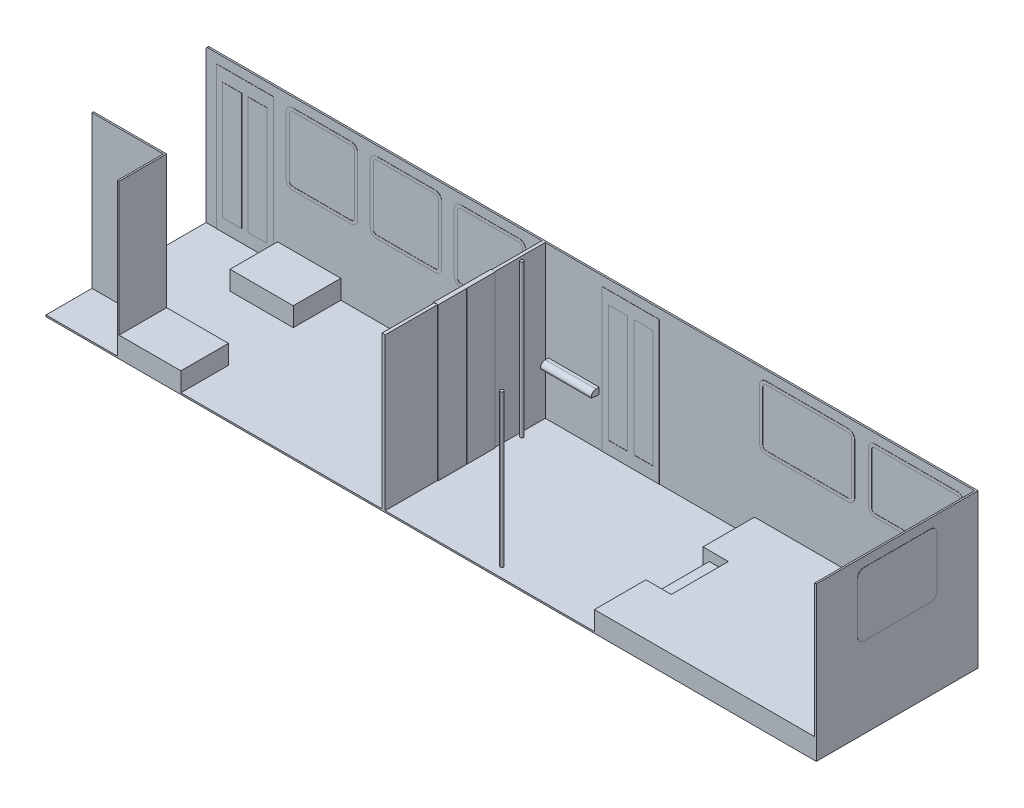
SolidWorks part; units mm, degrees
ref_plane "Front Plane" through (0, 0, 0) normal (0, 0, 1) x (1, 0, 0)
ref_plane "Top Plane" through (0, 0, 0) normal (0, 1, 0) x (1, 0, 0)
ref_plane "Right Plane" through (0, 0, 0) normal (1, 0, 0) x (0, 0, -1)
sketch "Sketch2" plane through (0, 0, 0) normal (0, 1, 0) x (1, 0, 0)
  line L1 (-6172.2, 1295.4) -> (6172.2, 1295.4)
  line L2 (-6172.2, 1295.4) -> (-6172.2, -1295.4)
  line L3 (-6172.2, -1295.4) -> (6172.2, -1295.4)
  line L4 (6172.2, 1295.4) -> (6172.2, -1295.4)
  line L5 (-6172.2, 1295.4) -> (6172.2, -1295.4) construction
  line L6 (-6172.2, -1295.4) -> (6172.2, 1295.4) construction
  point P0 (0, 0)
extrude "Boss-Extrude1" add sketch "Sketch2" along normal blind 25.4
sketch "Sketch3" plane through (0, 25.4, 0) normal (0, 1, 0) x (1, 0, 0)
  line L0 (-6172.2, -1295.4) -> (6172.2, -1295.4) construction
  line L4 (-787.4, 1295.4) -> (-787.4, -1295.4)
  line L6 (-787.4, 1295.4) -> (-736.6, 1295.4)
  line L7 (-787.4, 1295.4) -> (-787.4, -1295.4)
  line L8 (-787.4, -1295.4) -> (-736.6, -1295.4)
  line L9 (-736.6, 1295.4) -> (-736.6, -1295.4)
  line M2 (6172.2, 1295.4) -> (-6172.2, 1295.4)
  line M4 (-6172.2, -1295.4) -> (6172.2, -1295.4)
extrude "Boss-Extrude2" add sketch "Sketch3" along normal blind 2440.94 contours L9 L4 M2 M4
sketch "Sketch4" plane through (-736.6, 0, 0) normal (1, 0, 0) x (0, 0, -1)
  line L0 (1295.4, 2466.34) -> (-1295.4, 2466.34) construction
  line L1 (0, 2466.34) -> (457.2, 2466.34)
  line L2 (0, 2466.34) -> (0, 25.4)
  line L3 (0, 25.4) -> (457.2, 25.4)
  line L4 (457.2, 2466.34) -> (457.2, 25.4)
  line L5 (1295.4, 25.4) -> (-1295.4, 25.4) construction
  line L7 (0, 2466.34) -> (-457.2, 2466.34)
  line L8 (0, 2466.34) -> (0, 25.4)
  line L9 (0, 25.4) -> (-457.2, 25.4)
  line L10 (-457.2, 2466.34) -> (-457.2, 25.4)
  line M9 (-1295.4, 25.4) -> (1295.4, 25.4)
  line M11 (1295.4, 2466.34) -> (-1295.4, 2466.34)
extrude "Boss-Extrude4" add sketch "Sketch4" against normal blind 71.12 from offset 10.16 separate body contours L10 L2 M11 M9
sketch "Sketch5" plane through (-726.44, 0, 0) normal (1, 0, 0) x (0, 0, -1)
  line L1 (457.2, 2466.34) -> (-457.2, 2466.34) construction
  line L2 (-457.2, 25.4) -> (457.2, 25.4) construction
  line L3 (0, 25.4) -> (-6.35, 25.4)
  line L4 (-6.35, 25.4) -> (-6.35, 2466.34)
  line L5 (-6.35, 2466.34) -> (0, 2466.34)
  line L6 (0, 2466.34) -> (6.35, 2466.34)
  line L7 (6.35, 2466.34) -> (6.35, 25.4)
  line L8 (6.35, 25.4) -> (0, 25.4)
extrude "Cut-Extrude1" cut sketch "Sketch5" against normal blind 5.08
sketch "Sketch6" plane through (-731.52, 0, 0) normal (1, 0, 0) x (0, 0, -1)
  line L0 (-6.35, 25.4) -> (6.35, 25.4) construction
  line L1 (6.35, 2466.34) -> (-6.35, 2466.34)
  line L2 (6.35, 2466.34) -> (6.35, 25.4)
  line L3 (6.35, 25.4) -> (-6.35, 25.4)
  line L4 (-6.35, 2466.34) -> (-6.35, 25.4)
  line L5 (-6.35, 2466.34) -> (-6.35, 25.4) construction
extrude "Cut-Extrude2" cut sketch "Sketch6" along normal blind 5.08 from offset 66.04 offset against normal yes
sketch "Sketch8" plane through (0, 2466.34, 0) normal (0, 1, 0) x (1, 0, 0)
  line L0 (-797.56, 457.2) -> (-797.56, 6.35) construction
  line L1 (-726.44, -457.2) -> (-797.56, -457.2)
  line L2 (-726.44, -457.2) -> (-726.44, 457.2)
  line L3 (-726.44, 457.2) -> (-797.56, 457.2)
  line L4 (-797.56, -457.2) -> (-797.56, 457.2)
extrude "Boss-Extrude5" add sketch "Sketch8" along normal blind 2.54
sketch "Sketch9" plane through (0, 0, -1295.4) normal (0, 0, -1) x (-1, 0, 0)
  line L1 (736.6, 2466.34) -> (787.4, 2466.34)
  line L2 (736.6, 2466.34) -> (736.6, 25.4)
  line L3 (736.6, 25.4) -> (787.4, 25.4)
  line L4 (787.4, 2466.34) -> (787.4, 25.4)
extrude "Cut-Extrude4" cut sketch "Sketch9" against normal blind 25.4
sketch "Sketch11" plane through (0, 25.4, 0) normal (0, 1, 0) x (1, 0, 0)
  line L0 (6172.2, -1295.4) -> (6172.2, 1295.4) construction
  line L1 (-6172.2, 1295.4) -> (6172.2, 1295.4)
  line L2 (-6172.2, 1295.4) -> (-6172.2, 1270)
  line L3 (-6172.2, 1270) -> (6172.2, 1270)
  line L4 (6172.2, 1295.4) -> (6172.2, 1270)
  line L6 (-1128.2325, -4255.065) -> (-638.6774, -4255.065)
  line L7 (-1128.2325, -4255.065) -> (-1128.2325, -7837.6362)
  line L8 (-1128.2325, -7837.6362) -> (-638.6774, -7837.6362)
  line L9 (-638.6774, -4255.065) -> (-638.6774, -7837.6362)
extrude "Boss-Extrude6" add sketch "Sketch11" along normal blind 2438.4 contours L2 L1 L4 L3
fillet "Fillet1" radius 25.4 1 edges at (-6172.2, 2463.8, -1282.7)
sketch "Sketch12" plane through (0, 0, -1270) normal (0, 0, 1) x (1, 0, 0)
  line L0 (-6172.2, 25.4) -> (-787.4, 25.4) construction
  line L1 (-6003.7041, 25.4) -> (-5089.3041, 25.4)
  line L2 (-6003.7041, 25.4) -> (-6003.7041, 2311.4)
  line L3 (-6003.7041, 2311.4) -> (-5089.3041, 2311.4)
  line L4 (-5089.3041, 25.4) -> (-5089.3041, 2311.4)
extrude "Boss-Extrude7" add sketch "Sketch12" against normal blind 30.48 from offset 2.54 separate body contours L2 L1 L4 L3
sketch "Sketch13" plane through (0, 0, -1267.46) normal (0, 0, 1) x (1, 0, 0)
  line L0 (-6003.7041, 2311.4) -> (-5902.1041, 2311.4) construction
  line L1 (-6003.7041, 2311.4) -> (-5089.3041, 2311.4) construction
  line L2 (-5902.1041, 2108.2) -> (-5597.3041, 2108.2)
  line L3 (-5495.7041, 2108.2) -> (-5190.9041, 2108.2)
  line L4 (-5190.9041, 228.6) -> (-5190.9041, 2108.2) construction
  line L5 (-5190.9041, 228.6) -> (-5495.7041, 228.6)
  line L6 (-5597.3041, 228.6) -> (-5902.1041, 228.6)
  line L8 (-5902.1041, 2108.2) -> (-5902.1041, 228.6)
  line L10 (-5190.9041, 2108.2) -> (-5190.9041, 228.6)
  line L11 (-5597.3041, 228.6) -> (-5597.3041, 2108.2)
  line L13 (-5495.7041, 2108.2) -> (-5495.7041, 228.6)
extrude "Cut-Extrude5" cut sketch "Sketch13" against normal blind 99.06
sketch "Sketch17" plane through (0, 0, -1267.46) normal (0, 0, 1) x (1, 0, 0)
  line L1 (-5902.1041, 2108.2) -> (-5597.3041, 2108.2)
  line L2 (-5902.1041, 2108.2) -> (-5902.1041, 228.6)
  line L3 (-5902.1041, 228.6) -> (-5597.3041, 228.6)
  line L4 (-5597.3041, 2108.2) -> (-5597.3041, 228.6)
  line L5 (-5495.7041, 228.6) -> (-5190.9041, 228.6)
  line L6 (-5495.7041, 228.6) -> (-5495.7041, 2108.2)
  line L7 (-5495.7041, 2108.2) -> (-5190.9041, 2108.2)
  line L8 (-5190.9041, 228.6) -> (-5190.9041, 2108.2)
extrude "Boss-Extrude9" add sketch "Sketch17" against normal blind 25.4 from offset 2.54
sketch "Sketch20" plane through (0, 25.4, 0) normal (0, 1, 0) x (1, 0, 0)
  line L0 (-736.6, -1295.4) -> (6172.2, -1295.4) construction
  line L1 (6172.2, 1270) -> (2616.2, 1270)
  line L2 (6172.2, 1270) -> (6172.2, -1295.4)
  line L3 (6172.2, -1295.4) -> (2616.2, -1295.4)
  line L4 (2616.2, 1270) -> (2616.2, -1295.4)
extrude "Boss-Extrude10" add sketch "Sketch20" along normal blind 304.8
sketch "Sketch21" plane through (2616.2, 0, 0) normal (-1, 0, 0) x (0, 0, 1)
  line L0 (-1270, 330.2) -> (1295.4, 330.2) construction
  line L1 (12.7, 330.2) -> (12.7, 25.4) construction
  line L2 (-1270, 25.4) -> (1295.4, 25.4) construction
  line L4 (-444.5, 25.4) -> (469.9, 25.4)
  line L5 (-444.5, 25.4) -> (-444.5, 330.2)
  line L6 (-444.5, 330.2) -> (469.9, 330.2)
  line L7 (469.9, 25.4) -> (469.9, 330.2)
  line L8 (-444.5, 25.4) -> (469.9, 330.2) construction
  line L9 (-444.5, 330.2) -> (469.9, 25.4) construction
  point P8 (12.7, 177.8)
extrude "Cut-Extrude6" cut sketch "Sketch21" against normal blind 101.6
sketch "Sketch22" plane through (2717.8, 0, 0) normal (-1, 0, 0) x (0, 0, 1)
  line L0 (469.9, 25.4) -> (469.9, 330.2) construction
  line L1 (-444.5, 330.2) -> (469.9, 330.2)
  line L2 (-444.5, 330.2) -> (-444.5, 177.8)
  line L3 (-444.5, 177.8) -> (469.9, 177.8)
  line L4 (469.9, 330.2) -> (469.9, 177.8)
extrude "Cut-Extrude7" cut sketch "Sketch22" against normal blind 304.8
sketch "Sketch25" plane through (0, 0, -1270) normal (0, 0, 1) x (1, 0, 0)
  line L0 (-736.6, 25.4) -> (177.8, 25.4) construction
  line L1 (-736.6, 25.4) -> (2616.2, 25.4) construction
  line L3 (177.8, 25.4) -> (1092.2, 25.4)
  line L4 (177.8, 25.4) -> (177.8, 2311.4)
  line L5 (177.8, 2311.4) -> (1092.2, 2311.4)
  line L6 (1092.2, 25.4) -> (1092.2, 2311.4)
  line L11 (584.2, 228.6) -> (279.4, 228.6)
  line L12 (584.2, 228.6) -> (584.2, 2108.2)
  line L13 (584.2, 2108.2) -> (279.4, 2108.2)
  line L14 (279.4, 228.6) -> (279.4, 2108.2)
  line L15 (685.8, 2108.2) -> (990.6, 2108.2)
  line L16 (685.8, 2108.2) -> (685.8, 228.6)
  line L17 (685.8, 228.6) -> (990.6, 228.6)
  line L18 (990.6, 2108.2) -> (990.6, 228.6)
  point P8 (0, 0)
  point P9 (0, 0)
  point P10 (0, 0)
  point P13 (0, 0)
  point P14 (0, 0)
  point P22 (0, 0)
  point P23 (0, 0)
extrude "Boss-Extrude12" add sketch "Sketch25" against normal blind 27.94 from offset 2.54 separate body
sketch "Sketch27" plane through (0, 0, -1267.46) normal (0, 0, 1) x (1, 0, 0)
  line L1 (279.4, 2108.2) -> (584.2, 2108.2)
  line L2 (279.4, 2108.2) -> (279.4, 228.6)
  line L3 (279.4, 228.6) -> (584.2, 228.6)
  line L4 (584.2, 2108.2) -> (584.2, 228.6)
  line L5 (685.8, 228.6) -> (990.6, 228.6)
  line L6 (685.8, 228.6) -> (685.8, 2108.2)
  line L7 (685.8, 2108.2) -> (990.6, 2108.2)
  line L8 (990.6, 228.6) -> (990.6, 2108.2)
extrude "Boss-Extrude13" add sketch "Sketch27" against normal blind 27.94 from offset 2.54 contours L2 L1 L4 L3 offset against normal yes
sketch "Sketch28" plane through (0, 0, -1270) normal (0, 0, 1) x (1, 0, 0)
  line L0 (-736.6, 889) -> (-685.8, 889)
  line L2 (-401.0106, 787.4) -> (177.8, 787.4)
  line L3 (177.8, 25.4) -> (177.8, 2311.4) construction
  line L4 (177.8, 787.4) -> (177.8, 889)
  line L5 (177.8, 889) -> (-736.6, 889)
  line L6 (-736.6, 2463.8) -> (-736.6, 25.4) construction
  line L7 (-736.6, 889) -> (-736.6, 787.4)
  line L8 (-736.6, 787.4) -> (-401.0106, 787.4)
  line L9 (-685.8, 889) -> (-685.8, 787.4)
  line L10 (-685.8, 787.4) -> (127, 787.4)
  line L11 (127, 787.4) -> (127, 889)
  line L12 (-685.8, 889) -> (127, 889)
extrude "Boss-Extrude17" add sketch "Sketch28" along normal blind 127 contours L2 L11 L5 L9 L8
fillet "Fillet3" radius 76.2 1 edges at (-279.4, 889, -1143)
chamfer "Chamfer2" distance 101.6 distance2 12.7 1 edges at (-279.4, 787.4, -1143)
sketch "Sketch31" plane through (0, 25.4, 0) normal (0, 1, 0) x (1, 0, 0)
  circle A0 centre (-670.5546, 827.918) radius 25.4
  point P2 (-595.0728, 966.3361)
  point P3 (-629.9364, 737.5636)
  point P4 (-685.3283, 823.8649)
  point P5 (-670.5546, 827.918)
extrude "Boss-Extrude18" add sketch "Sketch31" along normal blind 2438.4 contours A0
sketch "Sketch32" plane through (0, 0, -1270) normal (0, 0, 1) x (1, 0, 0)
  line L0 (-5089.3041, 2311.4) -> (-787.4, 2311.4) construction
  line L1 (-787.4, 25.4) -> (-787.4, 2463.8) construction
  line L2 (-5089.3041, 2311.4) -> (-4886.1041, 2311.4) construction
  line L3 (-3743.1041, 1168.4) -> (-3539.9041, 1168.4) construction
  line L4 (-4784.5041, 2311.4) -> (-3844.7041, 2311.4)
  line L5 (-4886.1041, 2209.8) -> (-4886.1041, 1270)
  line L6 (-4784.5041, 1168.4) -> (-3844.7041, 1168.4)
  line L7 (-3743.1041, 2209.8) -> (-3743.1041, 1270)
  line L8 (-2396.9041, 1168.4) -> (-2193.7041, 1168.4) construction
  line L9 (-3438.3041, 1168.4) -> (-2498.5041, 1168.4)
  line L10 (-3539.9041, 1270) -> (-3539.9041, 2209.8)
  line L11 (-3438.3041, 2311.4) -> (-2498.5041, 2311.4)
  line L12 (-2396.9041, 1270) -> (-2396.9041, 2209.8)
  line L13 (-4835.3041, 2209.8) -> (-4835.3041, 1270)
  line L14 (-2092.1041, 1168.4) -> (-1152.3041, 1168.4)
  line L15 (-2193.7041, 1270) -> (-2193.7041, 2209.8)
  line L16 (-2092.1041, 2311.4) -> (-1152.3041, 2311.4)
  line L17 (-1050.7041, 1270) -> (-1050.7041, 2209.8)
  line L18 (-4784.5041, 1219.2) -> (-3844.7041, 1219.2)
  line L19 (-3793.9041, 2209.8) -> (-3793.9041, 1270)
  line L20 (-4784.5041, 2260.6) -> (-3844.7041, 2260.6)
  line L21 (-3489.1041, 1270) -> (-3489.1041, 2209.8)
  line L22 (-3438.3041, 2260.6) -> (-2498.5041, 2260.6)
  line L23 (-2447.7041, 1270) -> (-2447.7041, 2209.8)
  line L24 (-3438.3041, 1219.2) -> (-2498.5041, 1219.2)
  line L25 (-2142.9041, 1270) -> (-2142.9041, 2209.8)
  line L26 (-2092.1041, 2260.6) -> (-1152.3041, 2260.6)
  line L27 (-1101.5041, 1270) -> (-1101.5041, 2209.8)
  line L28 (-2092.1041, 1219.2) -> (-1152.3041, 1219.2)
  arc A0 (-4886.1041, 2209.8) -> (-4784.5041, 2311.4) centre (-4784.5041, 2209.8) cw
  arc A1 (-3844.7041, 1168.4) -> (-3743.1041, 1270) centre (-3844.7041, 1270) ccw
  arc A2 (-4886.1041, 1270) -> (-4784.5041, 1168.4) centre (-4784.5041, 1270) ccw
  arc A3 (-3844.7041, 2311.4) -> (-3743.1041, 2209.8) centre (-3844.7041, 2209.8) cw
  arc A4 (-1152.3041, 2311.4) -> (-1050.7041, 2209.8) centre (-1152.3041, 2209.8) cw
  arc A5 (-1152.3041, 1168.4) -> (-1050.7041, 1270) centre (-1152.3041, 1270) ccw
  arc A6 (-2193.7041, 1270) -> (-2092.1041, 1168.4) centre (-2092.1041, 1270) ccw
  arc A7 (-2193.7041, 2209.8) -> (-2092.1041, 2311.4) centre (-2092.1041, 2209.8) cw
  arc A8 (-2498.5041, 2311.4) -> (-2396.9041, 2209.8) centre (-2498.5041, 2209.8) cw
  arc A9 (-2498.5041, 1168.4) -> (-2396.9041, 1270) centre (-2498.5041, 1270) ccw
  arc A10 (-3539.9041, 1270) -> (-3438.3041, 1168.4) centre (-3438.3041, 1270) ccw
  arc A11 (-3539.9041, 2209.8) -> (-3438.3041, 2311.4) centre (-3438.3041, 2209.8) cw
  arc A12 (-4835.3041, 1270) -> (-4784.5041, 1219.2) centre (-4784.5041, 1270) ccw
  arc A13 (-3844.7041, 1219.2) -> (-3793.9041, 1270) centre (-3844.7041, 1270) ccw
  arc A14 (-3844.7041, 2260.6) -> (-3793.9041, 2209.8) centre (-3844.7041, 2209.8) cw
  arc A15 (-4835.3041, 2209.8) -> (-4784.5041, 2260.6) centre (-4784.5041, 2209.8) cw
  arc A16 (-3489.1041, 2209.8) -> (-3438.3041, 2260.6) centre (-3438.3041, 2209.8) cw
  arc A17 (-2498.5041, 2260.6) -> (-2447.7041, 2209.8) centre (-2498.5041, 2209.8) cw
  arc A18 (-2498.5041, 1219.2) -> (-2447.7041, 1270) centre (-2498.5041, 1270) ccw
  arc A19 (-3489.1041, 1270) -> (-3438.3041, 1219.2) centre (-3438.3041, 1270) ccw
  arc A20 (-2142.9041, 2209.8) -> (-2092.1041, 2260.6) centre (-2092.1041, 2209.8) cw
  arc A21 (-1152.3041, 2260.6) -> (-1101.5041, 2209.8) centre (-1152.3041, 2209.8) cw
  arc A22 (-1152.3041, 1219.2) -> (-1101.5041, 1270) centre (-1152.3041, 1270) ccw
  arc A23 (-2142.9041, 1270) -> (-2092.1041, 1219.2) centre (-2092.1041, 1270) ccw
  point P17 (0, 0)
  point P30 (-1050.7041, 2311.4)
  point P40 (-2396.9041, 2311.4)
  dimension "D1" = 101.6
  dimension "D2" = 101.6
  dimension "D3" = 101.6
  dimension "D4" = 50.8
  dimension "D5" = 50.8
  dimension "D6" = 50.8
extrude "Boss-Extrude19" add sketch "Sketch32" against normal blind 30.48 from offset 2.54 contours A11 L10 A10 L9 A9 L12 A8 L11 | A7 L15 A6 L14 A5 L17 A4 L16 | L5 A2 L6 A1 L7 A3 L4 A0
sketch3d "3DSketch1" plane through (0, 0, 0) normal (0, 0, 1) x (1, 0, 0)
sketch3d "3DSketch2" plane through (0, 0, 0) normal (0, 0, 1) x (1, 0, 0)
sketch "Sketch34" plane through (0, 0, -1267.46) normal (0, 0, 1) x (1, 0, 0)
  line L12 (-4835.3041, 2209.8) -> (-4835.3041, 1270)
  line L13 (-4784.5041, 1219.2) -> (-3844.7041, 1219.2)
  line L14 (-3793.9041, 1270) -> (-3793.9041, 2209.8)
  line L15 (-3844.7041, 2260.6) -> (-4784.5041, 2260.6)
  arc A12 (-4784.5041, 2260.6) -> (-4835.3041, 2209.8) centre (-4784.5041, 2209.8) ccw
  arc A13 (-4835.3041, 1270) -> (-4784.5041, 1219.2) centre (-4784.5041, 1270) ccw
  arc A14 (-3844.7041, 1219.2) -> (-3793.9041, 1270) centre (-3844.7041, 1270) ccw
  arc A15 (-3793.9041, 2209.8) -> (-3844.7041, 2260.6) centre (-3844.7041, 2209.8) ccw
extrude "Cut-Extrude8" cut sketch "Sketch34" against normal blind 2.54
sketch "Sketch35" plane through (0, 0, -1270) normal (0, 0, 1) x (1, 0, 0)
  line L1 (6172.2, 2463.8) -> (6172.2, 330.2) construction
  line L2 (6172.2, 2311.4) -> (5969, 2311.4) construction
  line L4 (5867.4, 2311.4) -> (4546.6, 2311.4)
  line L5 (5969, 2209.8) -> (5969, 1397)
  line L6 (5867.4, 1295.4) -> (4546.6, 1295.4)
  line L7 (4445, 2209.8) -> (4445, 1397)
  line L10 (4122.1853, 1295.4) -> (2801.3853, 1295.4)
  line L11 (4223.7853, 1397) -> (4223.7853, 2209.8)
  line L12 (4122.1853, 2311.4) -> (2801.3853, 2311.4)
  line L13 (2699.7853, 1397) -> (2699.7853, 2209.8)
  arc A0 (5969, 2209.8) -> (5867.4, 2311.4) centre (5867.4, 2209.8) ccw
  arc A1 (5969, 1397) -> (5867.4, 1295.4) centre (5867.4, 1397) cw
  arc A2 (4546.6, 1295.4) -> (4445, 1397) centre (4546.6, 1397) cw
  arc A3 (4546.6, 2311.4) -> (4445, 2209.8) centre (4546.6, 2209.8) ccw
  arc A4 (4223.7853, 2209.8) -> (4122.1853, 2311.4) centre (4122.1853, 2209.8) ccw
  arc A5 (4223.7853, 1397) -> (4122.1853, 1295.4) centre (4122.1853, 1397) cw
  arc A6 (2801.3853, 1295.4) -> (2699.7853, 1397) centre (2801.3853, 1397) cw
  arc A7 (2801.3853, 2311.4) -> (2699.7853, 2209.8) centre (2801.3853, 2209.8) ccw
  dimension "D1" = 101.6
extrude "Boss-Extrude22" add sketch "Sketch35" against normal blind 30.48 from offset 2.54
sketch "Sketch37" plane through (0, 0, -1267.46) normal (0, 0, 1) x (1, 0, 0)
  line L8 (4122.1853, 2260.6) -> (2801.3853, 2260.6)
  line L9 (2750.5853, 2209.8) -> (2750.5853, 1397)
  line L10 (2801.3853, 1346.2) -> (4122.1853, 1346.2)
  line L11 (4172.9853, 1397) -> (4172.9853, 2209.8)
  line L12 (4122.1853, 2260.6) -> (2801.3853, 2260.6)
  line L13 (2750.5853, 2209.8) -> (2750.5853, 1397)
  line L14 (2801.3853, 1346.2) -> (4122.1853, 1346.2)
  line L15 (4172.9853, 1397) -> (4172.9853, 2209.8)
  line L20 (5867.4, 2260.6) -> (4546.6, 2260.6)
  line L21 (4495.8, 2209.8) -> (4495.8, 1397)
  line L22 (4546.6, 1346.2) -> (5867.4, 1346.2)
  line L23 (5918.2, 1397) -> (5918.2, 2209.8)
  line L24 (5867.4, 2260.6) -> (4546.6, 2260.6)
  line L25 (4495.8, 2209.8) -> (4495.8, 1397)
  line L26 (4546.6, 1346.2) -> (5867.4, 1346.2)
  line L27 (5918.2, 1397) -> (5918.2, 2209.8)
  arc A8 (4172.9853, 2209.8) -> (4122.1853, 2260.6) centre (4122.1853, 2209.8) ccw
  arc A9 (2801.3853, 2260.6) -> (2750.5853, 2209.8) centre (2801.3853, 2209.8) ccw
  arc A10 (2750.5853, 1397) -> (2801.3853, 1346.2) centre (2801.3853, 1397) ccw
  arc A11 (4122.1853, 1346.2) -> (4172.9853, 1397) centre (4122.1853, 1397) ccw
  arc A12 (4172.9853, 2209.8) -> (4122.1853, 2260.6) centre (4122.1853, 2209.8) ccw
  arc A13 (2801.3853, 2260.6) -> (2750.5853, 2209.8) centre (2801.3853, 2209.8) ccw
  arc A14 (2750.5853, 1397) -> (2801.3853, 1346.2) centre (2801.3853, 1397) ccw
  arc A15 (4122.1853, 1346.2) -> (4172.9853, 1397) centre (4122.1853, 1397) ccw
  arc A20 (5918.2, 2209.8) -> (5867.4, 2260.6) centre (5867.4, 2209.8) ccw
  arc A21 (4546.6, 2260.6) -> (4495.8, 2209.8) centre (4546.6, 2209.8) ccw
  arc A22 (4495.8, 1397) -> (4546.6, 1346.2) centre (4546.6, 1397) ccw
  arc A23 (5867.4, 1346.2) -> (5918.2, 1397) centre (5867.4, 1397) ccw
  arc A24 (5918.2, 2209.8) -> (5867.4, 2260.6) centre (5867.4, 2209.8) ccw
  arc A25 (4546.6, 2260.6) -> (4495.8, 2209.8) centre (4546.6, 2209.8) ccw
  arc A26 (4495.8, 1397) -> (4546.6, 1346.2) centre (4546.6, 1397) ccw
  arc A27 (5867.4, 1346.2) -> (5918.2, 1397) centre (5867.4, 1397) ccw
  dimension "D1" = 50.8
  dimension "D2" = 50.8
extrude "Cut-Extrude10" cut sketch "Sketch37" against normal blind 2.54 contours L26 A27 L27 A24 L24 A25 L25 A26 | A12 L12 A13 L13 A14 L14 A15 L15
sketch "Sketch38" plane through (0, 25.4, 0) normal (0, 1, 0) x (1, 0, 0)
  circle A0 centre (969.6512, -1131.5574) radius 25.4
  point P2 (913.361, -1027.1569)
  point P3 (910.198, -884.2055)
  point P4 (945.0703, -858.1775)
  point P5 (929.3007, -695.3816)
  point P6 (962.8331, -1078.8647)
  point P7 (0, 0)
  point P8 (969.6512, -1131.5574)
extrude "Boss-Extrude23" add sketch "Sketch38" along normal blind 2438.4
sketch "Sketch39" plane through (0, 25.4, 0) normal (0, 1, 0) x (1, 0, 0)
  line L0 (-6172.2, 1270) -> (-5026.3967, 1270) construction
  line L1 (-5089.3041, 1270) -> (-787.4, 1270) construction
  line L2 (-5026.3967, 1270) -> (-5026.3967, -1295.4) construction
  line L3 (-6172.2, -1295.4) -> (-787.4, -1295.4) construction
  line L5 (-5026.3967, 1270) -> (-4013.2, 1270)
  line L6 (-5026.3967, 1270) -> (-5026.3967, 508)
  line L7 (-5026.3967, 508) -> (-4013.2, 508)
  line L8 (-4013.2, 1270) -> (-4013.2, 508)
  line L9 (-5026.3967, -1295.4) -> (-4010.3967, -1295.4)
  line L10 (-5026.3967, -1295.4) -> (-5026.3967, -533.4)
  line L11 (-5026.3967, -533.4) -> (-4010.3967, -533.4)
  line L12 (-4010.3967, -1295.4) -> (-4010.3967, -533.4)
extrude "Boss-Extrude24" add sketch "Sketch39" along normal blind 304.8
sketch "Sketch41" plane through (0, 330.2, 0) normal (0, 1, 0) x (1, 0, 0)
  line L0 (-5026.3967, -1295.4) -> (-4010.3967, -1295.4) construction
  line L1 (-5026.3967, -533.4) -> (-5000.9967, -533.4)
  line L2 (-5026.3967, -533.4) -> (-5026.3967, -1295.4)
  line L3 (-5026.3967, -1295.4) -> (-5000.9967, -1295.4)
  line L4 (-5000.9967, -533.4) -> (-5000.9967, -1295.4)
extrude "Boss-Extrude25" add sketch "Sketch41" along normal blind 2133.6 separate body
sketch "Sketch42" plane through (0, 25.4, 0) normal (0, 1, 0) x (1, 0, 0)
  line L0 (-6172.2, 1270) -> (-6172.2, -1295.4) construction
  line L1 (-5026.3967, -533.4) -> (-6172.2, -533.4)
  line L2 (-5026.3967, -533.4) -> (-5026.3967, -558.8)
  line L3 (-5026.3967, -558.8) -> (-6172.2, -558.8)
  line L4 (-6172.2, -533.4) -> (-6172.2, -558.8)
extrude "Boss-Extrude26" add sketch "Sketch42" along normal blind 2438.4 separate body
sketch "Sketch43" plane through (0, 330.2, 0) normal (0, 1, 0) x (1, 0, 0)
  line L0 (6172.2, 1270) -> (2616.2, 1270) construction
  line L1 (6172.2, -1295.4) -> (6146.8, -1295.4)
  line L2 (6172.2, -1295.4) -> (6172.2, 1270)
  line L3 (6172.2, 1270) -> (6146.8, 1270)
  line L4 (6146.8, -1295.4) -> (6146.8, 1270)
extrude "Boss-Extrude27" add sketch "Sketch43" along normal blind 2133.6
sketch "Sketch44" plane through (6146.8, 0, 0) normal (-1, 0, 0) x (0, 0, 1)
  line L0 (-1270, 2463.8) -> (12.7, 2463.8) construction
  line L1 (-1270, 2463.8) -> (1295.4, 2463.8) construction
  line L2 (12.7, 2463.8) -> (12.7, 2311.4) construction
  line L3 (12.7, 2311.4) -> (635, 2311.4) construction
  line L5 (533.4, 2311.4) -> (-533.4, 2311.4)
  line L6 (635, 2209.8) -> (635, 1397)
  line L7 (533.4, 1295.4) -> (-533.4, 1295.4)
  line L8 (-635, 2209.8) -> (-635, 1397)
  arc A0 (635, 2209.8) -> (533.4, 2311.4) centre (533.4, 2209.8) ccw
  arc A1 (635, 1397) -> (533.4, 1295.4) centre (533.4, 1397) cw
  arc A2 (-533.4, 1295.4) -> (-635, 1397) centre (-533.4, 1397) cw
  arc A3 (-533.4, 2311.4) -> (-635, 2209.8) centre (-533.4, 2209.8) ccw
  dimension "D1" = 101.6
sketch "Sketch45" plane through (0, 0, -1270) normal (0, 0, 1) x (1, 0, 0)
extrude "Boss-Extrude28" add sketch "Sketch44" against normal blind 30.48 from offset 2.54
sketch "Sketch47" plane through (6144.26, 0, 0) normal (-1, 0, 0) x (0, 0, 1)
  line L8 (533.4, 2260.6) -> (-533.4, 2260.6)
  line L9 (-584.2, 2209.8) -> (-584.2, 1397)
  line L10 (-533.4, 1346.2) -> (533.4, 1346.2)
  line L11 (584.2, 1397) -> (584.2, 2209.8)
  line L12 (533.4, 2260.6) -> (-533.4, 2260.6)
  line L13 (-584.2, 2209.8) -> (-584.2, 1397)
  line L14 (-533.4, 1346.2) -> (533.4, 1346.2)
  line L15 (584.2, 1397) -> (584.2, 2209.8)
  arc A8 (584.2, 2209.8) -> (533.4, 2260.6) centre (533.4, 2209.8) ccw
  arc A9 (-533.4, 2260.6) -> (-584.2, 2209.8) centre (-533.4, 2209.8) ccw
  arc A10 (-584.2, 1397) -> (-533.4, 1346.2) centre (-533.4, 1397) ccw
  arc A11 (533.4, 1346.2) -> (584.2, 1397) centre (533.4, 1397) ccw
  arc A12 (584.2, 2209.8) -> (533.4, 2260.6) centre (533.4, 2209.8) ccw
  arc A13 (-533.4, 2260.6) -> (-584.2, 2209.8) centre (-533.4, 2209.8) ccw
  arc A14 (-584.2, 1397) -> (-533.4, 1346.2) centre (-533.4, 1397) ccw
  arc A15 (533.4, 1346.2) -> (584.2, 1397) centre (533.4, 1397) ccw
  dimension "D1" = 50.8
extrude "Cut-Extrude11" cut sketch "Sketch47" against normal blind 2.54
